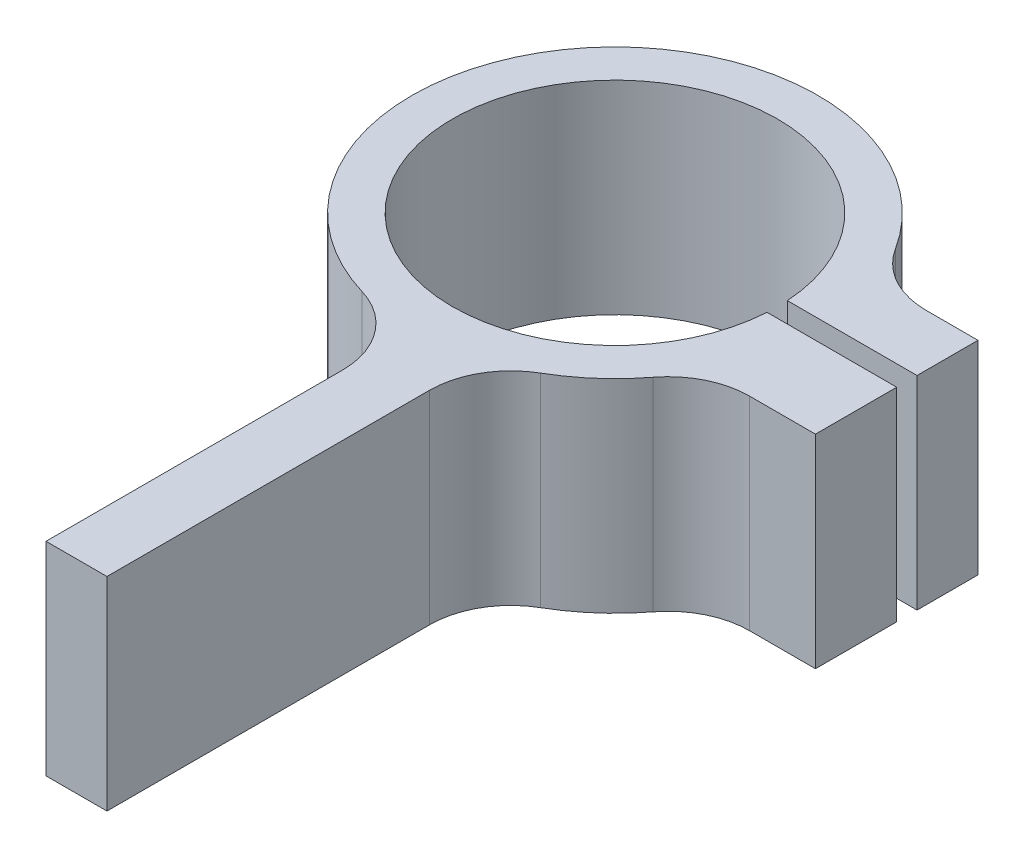
SolidWorks part; units mm, degrees
ref_plane "Front Plane" through (0, 0, 0) normal (0, 0, 1) x (1, 0, 0)
ref_plane "Top Plane" through (0, 0, 0) normal (0, 1, 0) x (1, 0, 0)
ref_plane "Right Plane" through (0, 0, 0) normal (1, 0, 0) x (0, 0, -1)
sketch "Sketch1" plane through (0, 0, 0) normal (0, 1, 0) x (1, 0, 0)
  line L0 (0, -10) -> (0, -28)
  line L1 (0, -28) -> (3, -28)
  line L2 (3, -28) -> (3, -9.5394)
  line L3 (7.9844, 0.5) -> (9.9875, 0.5)
  line L4 (7.9844, -0.5) -> (9.9875, -0.5)
  line L5 (9.9875, 0.5) -> (14.3675, 0.5)
  line L6 (14.3675, 0.5) -> (14.3675, 3.5)
  line L7 (14.3675, 3.5) -> (9.3675, 3.5)
  line L8 (9.9875, -0.5) -> (14.3675, -0.5)
  line L9 (14.3675, -0.5) -> (14.3675, -4.5)
  line L10 (14.3675, -4.5) -> (8.9303, -4.5)
  arc A0 (7.9844, 0.5) -> (7.9844, -0.5) centre (0, 0) ccw
  arc A1 (3, -9.5394) -> (8.9303, -4.5) centre (0, 0) ccw
  arc A2 (9.3675, 3.5) -> (0, -10) centre (0, 0) ccw
  dimension "D1" = 3
  dimension "D6" = 10
  dimension "D7" = 8
  dimension "D2" = 18
  dimension "D3" = 0.5
  dimension "D4" = 0.5
  dimension "D5" = 4
  dimension "D8" = 3
  dimension "D9" = 5
  dimension "D10" = 5
extrude "Boss-Extrude1" add sketch "Sketch1" along normal blind 10
fillet "Fillet1" radius 4 4 edges at (9.3675, 5, -3.5) (8.9303, 5, 4.5) (3, 5, 9.5394) (0, 5, 10)
